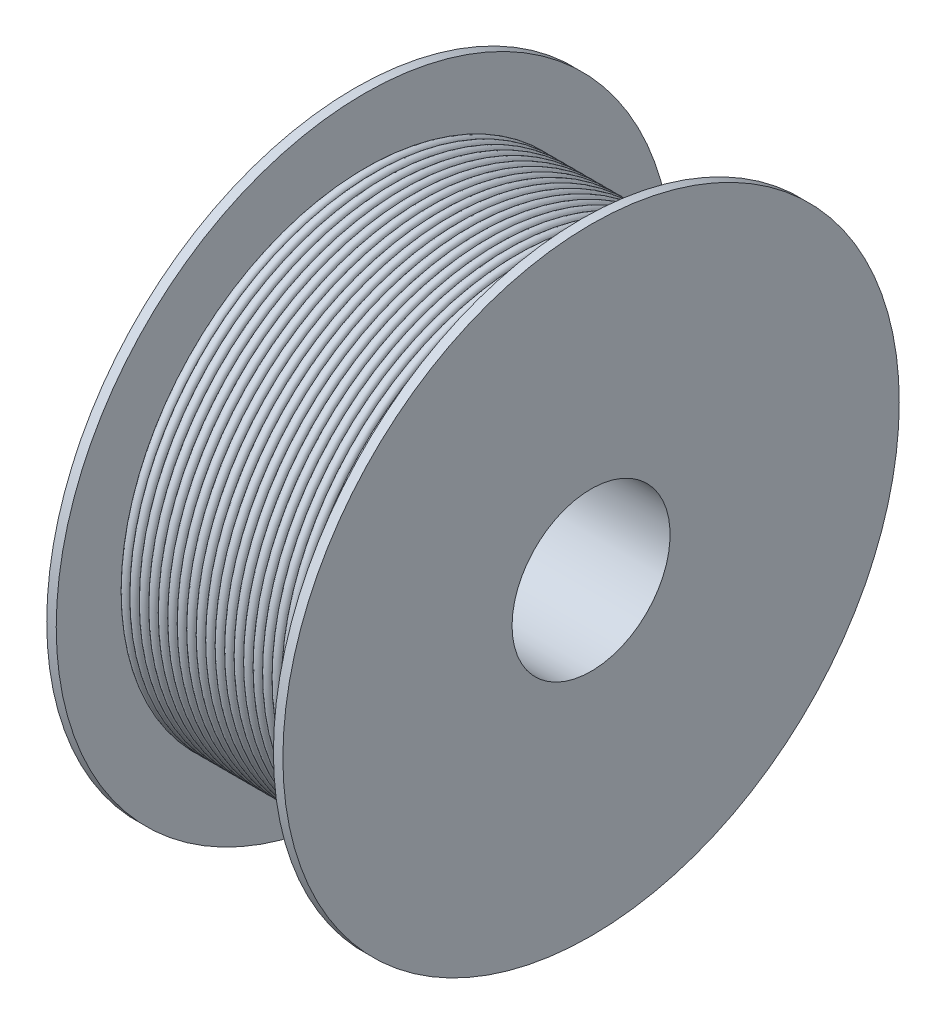
SolidWorks part; units mm, degrees
ref_plane "Front Plane" through (0, 0, 0) normal (0, 0, 1) x (1, 0, 0)
ref_plane "Top Plane" through (0, 0, 0) normal (0, 1, 0) x (1, 0, 0)
ref_plane "Right Plane" through (0, 0, 0) normal (1, 0, 0) x (0, 0, -1)
sketch "Sketch1" plane through (0, 0, 0) normal (0, 1, 0) x (1, 0, 0)
  line L0 (0, 58.783) -> (0, 131.283)
  line L1 (0, 131.283) -> (3, 131.283)
  line L2 (3, 131.283) -> (3, 110.1891)
  line L4 (71.7075, 110.1891) -> (71.7075, 131.283)
  line L5 (71.7075, 131.283) -> (74.7075, 131.283)
  line L6 (74.7075, 131.283) -> (74.7075, 58.783)
  line L7 (74.7075, 58.783) -> (0, 58.783)
  line L8 (-2.3274, 33.783) -> (77, 33.783) construction
  line L9 (71.4892, 110.1891) -> (71.7075, 110.1891)
  line L10 (68.4892, 110.1891) -> (68.7446, 110.1891)
  line L11 (65.4892, 110.1891) -> (65.7446, 110.1891)
  line L12 (62.4892, 110.1891) -> (62.7446, 110.1891)
  line L13 (59.4892, 110.1891) -> (59.7446, 110.1891)
  line L14 (56.4892, 110.1891) -> (56.7446, 110.1891)
  line L15 (53.4892, 110.1891) -> (53.7446, 110.1891)
  line L16 (44.4892, 110.1891) -> (44.7446, 110.1891)
  line L17 (47.4892, 110.1891) -> (47.7446, 110.1891)
  line L18 (50.4892, 110.1891) -> (50.7446, 110.1891)
  line L19 (41.4892, 110.1891) -> (41.7446, 110.1891)
  line L20 (38.4892, 110.1891) -> (38.7446, 110.1891)
  line L21 (35.4892, 110.1891) -> (35.7446, 110.1891)
  line L22 (32.4892, 110.1891) -> (32.7446, 110.1891)
  line L23 (29.4892, 110.1891) -> (29.7446, 110.1891)
  line L24 (26.4892, 110.1891) -> (26.7446, 110.1891)
  line L25 (23.4892, 110.1891) -> (23.7446, 110.1891)
  line L26 (20.4892, 110.1891) -> (20.7446, 110.1891)
  line L27 (17.4892, 110.1891) -> (17.7446, 110.1891)
  line L28 (14.4892, 110.1891) -> (14.7446, 110.1891)
  line L29 (11.4892, 110.1891) -> (11.7446, 110.1891)
  line L30 (8.4892, 110.1891) -> (8.7446, 110.1891)
  arc A0 (3, 110.1891) -> (5.7446, 110.1891) centre (4.3723, 110.1891) cw
  arc A1 (5.7446, 110.1891) -> (8.4892, 110.1891) centre (7.1169, 110.1891) cw
  arc A2 (8.7446, 110.1891) -> (11.4892, 110.1891) centre (10.1169, 110.1891) cw
  arc A3 (11.7446, 110.1891) -> (14.4892, 110.1891) centre (13.1169, 110.1891) cw
  arc A4 (14.7446, 110.1891) -> (17.4892, 110.1891) centre (16.1169, 110.1891) cw
  arc A5 (17.7446, 110.1891) -> (20.4892, 110.1891) centre (19.1169, 110.1891) cw
  arc A6 (20.7446, 110.1891) -> (23.4892, 110.1891) centre (22.1169, 110.1891) cw
  arc A7 (23.7446, 110.1891) -> (26.4892, 110.1891) centre (25.1169, 110.1891) cw
  arc A8 (26.7446, 110.1891) -> (29.4892, 110.1891) centre (28.1169, 110.1891) cw
  arc A9 (29.7446, 110.1891) -> (32.4892, 110.1891) centre (31.1169, 110.1891) cw
  arc A10 (32.7446, 110.1891) -> (35.4892, 110.1891) centre (34.1169, 110.1891) cw
  arc A11 (35.7446, 110.1891) -> (38.4892, 110.1891) centre (37.1169, 110.1891) cw
  arc A12 (38.7446, 110.1891) -> (41.4892, 110.1891) centre (40.1169, 110.1891) cw
  arc A13 (41.7446, 110.1891) -> (44.4892, 110.1891) centre (43.1169, 110.1891) cw
  arc A14 (44.7446, 110.1891) -> (47.4892, 110.1891) centre (46.1169, 110.1891) cw
  arc A15 (47.7446, 110.1891) -> (50.4892, 110.1891) centre (49.1169, 110.1891) cw
  arc A16 (50.7446, 110.1891) -> (53.4892, 110.1891) centre (52.1169, 110.1891) cw
  arc A17 (53.7446, 110.1891) -> (56.4892, 110.1891) centre (55.1169, 110.1891) cw
  arc A18 (56.7446, 110.1891) -> (59.4892, 110.1891) centre (58.1169, 110.1891) cw
  arc A19 (59.7446, 110.1891) -> (62.4892, 110.1891) centre (61.1169, 110.1891) cw
  arc A20 (62.7446, 110.1891) -> (65.4892, 110.1891) centre (64.1169, 110.1891) cw
  arc A21 (65.7446, 110.1891) -> (68.4892, 110.1891) centre (67.1169, 110.1891) cw
  arc A22 (68.7446, 110.1891) -> (71.4892, 110.1891) centre (70.1169, 110.1891) cw
  dimension "D1" = 97.5
  dimension "D2" = 25
  dimension "D3" = 3
  dimension "D4" = 3
  dimension "D5" = 22
revolve "Revolve1" add sketch "Sketch1" angle 360 about L8
